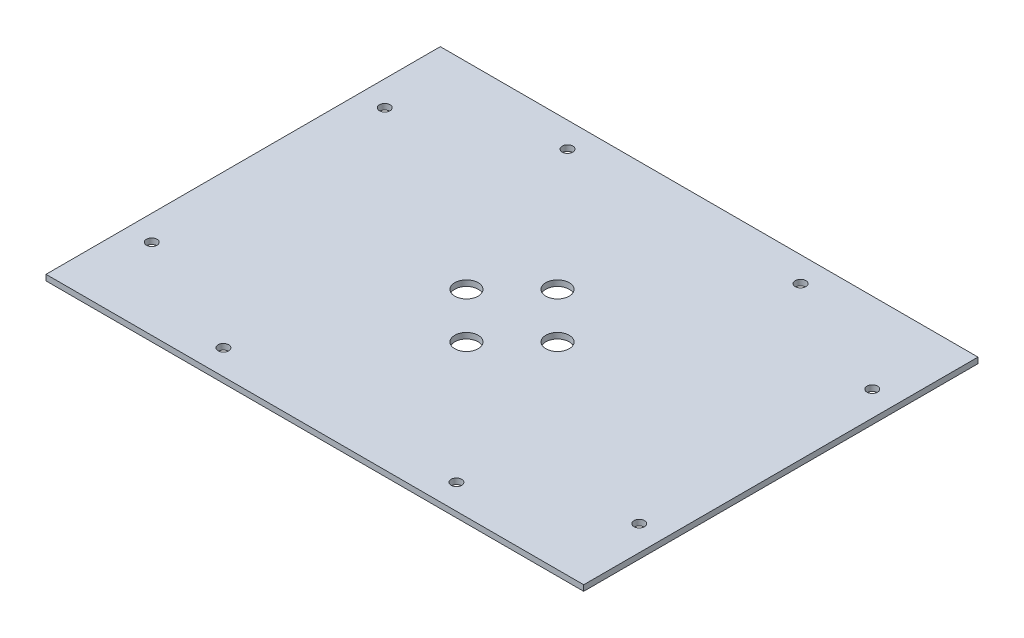
SolidWorks part; units mm, degrees
material "5052-H32"
ref_plane "Front Plane" through (0, 0, 0) normal (0, 0, 1) x (1, 0, 0)
ref_plane "Top Plane" through (0, 0, 0) normal (0, 1, 0) x (1, 0, 0)
ref_plane "Right Plane" through (0, 0, 0) normal (1, 0, 0) x (0, 0, -1)
sketch "Sketch1" plane through (0, 0, 0) normal (0, 1, 0) x (1, 0, 0)
  line L0 (0, 12.7) -> (0, -12.7) construction
  line L1 (-75, 55) -> (75, 55)
  line L2 (-75, 55) -> (-75, -55)
  line L3 (-75, -55) -> (75, -55)
  line L4 (75, 55) -> (75, -55)
  line L5 (-12.7, 0) -> (12.7, 0) construction
  line L7 (-32.5, 48) -> (32.5, 48) construction
  line L8 (-32.5, 48) -> (-32.5, -48) construction
  line L9 (-32.5, -48) -> (32.5, -48) construction
  line L10 (32.5, 48) -> (32.5, -48) construction
  line L11 (-68, 32.5) -> (68, 32.5) construction
  line L12 (-68, 32.5) -> (-68, -32.5) construction
  line L13 (-68, -32.5) -> (68, -32.5) construction
  line L14 (0, 55) -> (0, -55) construction
  line L15 (68, 32.5) -> (68, -32.5) construction
  circle A3 centre (0, 12.7) radius 3.2639
  circle A4 centre (12.7, 0) radius 3.2639
  circle A5 centre (0, -12.7) radius 3.2639
  circle A6 centre (-12.7, 0) radius 3.2639
  circle A30 centre (-32.5, 48) radius 1.4732
  circle A31 centre (32.5, 48) radius 1.4732
  circle A32 centre (32.5, -48) radius 1.4732
  circle A33 centre (-32.5, -48) radius 1.4732
  circle A34 centre (-68, 32.5) radius 1.4732
  circle A35 centre (68, 32.5) radius 1.4732
  circle A36 centre (68, -32.5) radius 1.4732
  circle A37 centre (-68, -32.5) radius 1.4732
  point P16 (0, 0)
  point P48 (0, 55)
  point P49 (75, 0)
  dimension "D4" = 6.5278
  dimension "D2" = 2.9464
  dimension "D1" = 25.4
  dimension "D7" = 150
  dimension "D3" = 65
  dimension "D5" = 42.5
  dimension "D8" = 110
  dimension "D9" = 7
  dimension "D10" = 7
  dimension "D11" = 7
  dimension "D12" = 7
  dimension "D13" = 65
  dimension "D14" = 22.5
  dimension "D6" = 4
extrude "Boss-Extrude1" add sketch "Sketch1" along normal blind 1.6
equation "\"D5@Sketch1\"=(\"D7@Sketch1\"-\"D3@Sketch1\")/2"
equation "\"D10@Sketch1\"=\"D9@Sketch1\""
equation "\"D11@Sketch1\"=\"D9@Sketch1\""
equation "\"D12@Sketch1\"=\"D11@Sketch1\""
equation "\"D14@Sketch1\"=(\"D8@Sketch1\"-\"D13@Sketch1\")/2"
